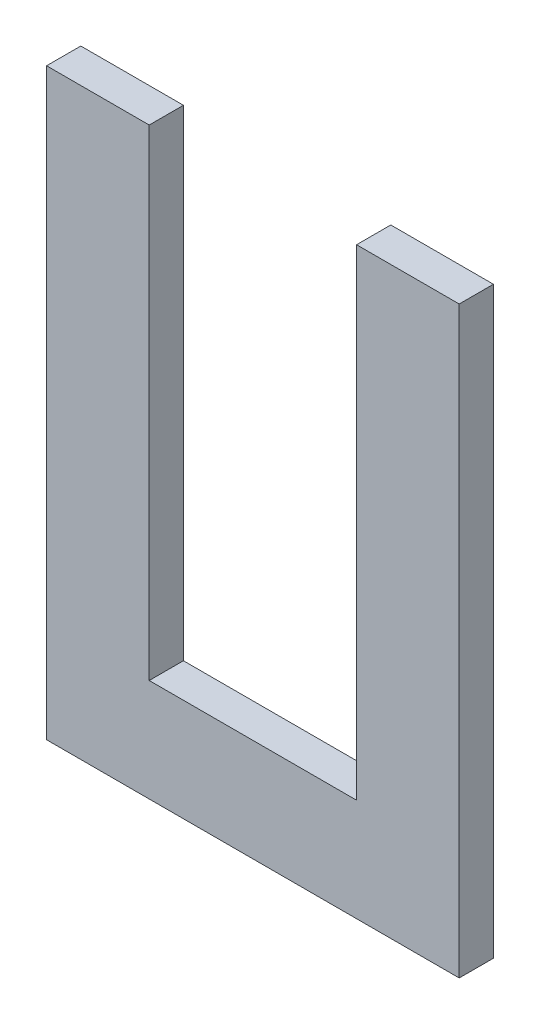
SolidWorks part; units mm, degrees
ref_plane "Alzado" through (0, 0, 0) normal (0, 0, 1) x (1, 0, 0)
ref_plane "Planta" through (0, 0, 0) normal (0, 1, 0) x (1, 0, 0)
ref_plane "Vista lateral" through (0, 0, 0) normal (1, 0, 0) x (0, 0, -1)
sketch "Croquis1" plane through (0, 0, 0) normal (0, 0, 1) x (1, 0, 0)
  line L0 (-162.4919, -715.7327) -> (-177.4919, -715.7327)
  line L2 (-162.4919, -715.7327) -> (-162.4919, -786.0327)
  line L3 (-162.4919, -786.0327) -> (-132.1919, -786.0327)
  line L4 (-132.1919, -715.7327) -> (-132.1919, -786.0327)
  line L5 (-177.4919, -715.7327) -> (-177.4919, -801.0327)
  line L6 (-177.4919, -801.0327) -> (-117.1919, -801.0327)
  line L7 (-117.1919, -801.0327) -> (-117.1919, -715.7327)
  line L8 (-117.1919, -715.7327) -> (-132.1919, -715.7327)
  dimension "D1" = 30.3
  dimension "D2" = 70.3
  dimension "D3" = 15
  dimension "D4" = 15
  dimension "D5" = 15
extrude "Saliente-Extruir1" add sketch "Croquis1" along normal blind 5
